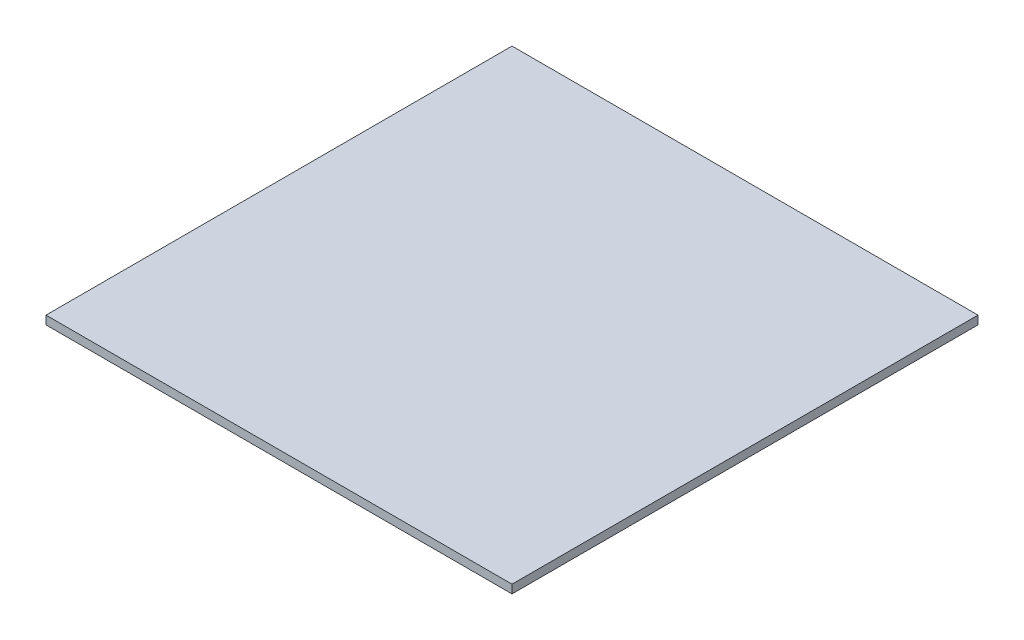
SolidWorks part; units mm, degrees
ref_plane "Front Plane" through (0, 0, 0) normal (0, 0, 1) x (1, 0, 0)
ref_plane "Top Plane" through (0, 0, 0) normal (0, 1, 0) x (1, 0, 0)
ref_plane "Right Plane" through (0, 0, 0) normal (1, 0, 0) x (0, 0, -1)
sketch "Sketch1" plane through (0, 0, 0) normal (0, 1, 0) x (1, 0, 0)
  line L1 (0, 0) -> (220, 0)
  line L2 (0, 0) -> (0, 220)
  line L3 (0, 220) -> (220, 220)
  line L4 (220, 0) -> (220, 220)
  dimension "D1" = 220
  dimension "D2" = 220
extrude "Boss-Extrude1" add sketch "Sketch1" along normal blind 4
